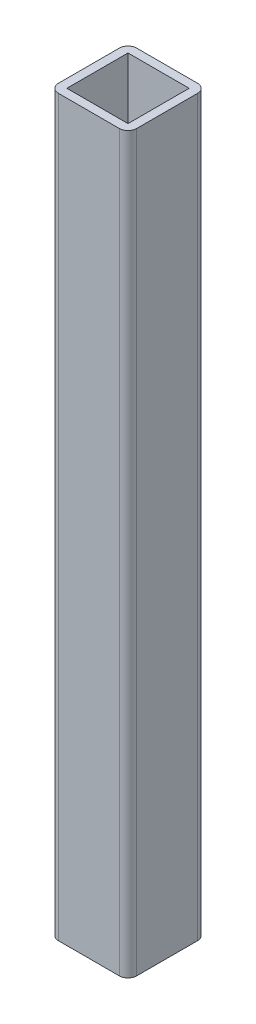
SolidWorks part; units mm, degrees
material "Plain Carbon Steel"
ref_plane "Front Plane" through (0, 0, 0) normal (0, 0, 1) x (1, 0, 0)
ref_plane "Top Plane" through (0, 0, 0) normal (0, 1, 0) x (1, 0, 0)
ref_plane "Right Plane" through (0, 0, 0) normal (1, 0, 0) x (0, 0, -1)
sketch "Sketch1" plane through (0, 0, 0) normal (0, 1, 0) x (1, 0, 0)
  line L1 (2.8, 0) -> (22.8, 0)
  line L2 (0, -2.8) -> (0, -22.8)
  line L3 (2.8, -25.6) -> (22.8, -25.6)
  line L4 (25.6, -2.8) -> (25.6, -22.8)
  arc A0 (22.8, 0) -> (25.6, -2.8) centre (22.8, -2.8) cw
  arc A1 (22.8, -25.6) -> (25.6, -22.8) centre (22.8, -22.8) ccw
  arc A2 (0, -22.8) -> (2.8, -25.6) centre (2.8, -22.8) ccw
  arc A3 (2.8, 0) -> (0, -2.8) centre (2.8, -2.8) ccw
  point P7 (25.6, 0)
  point P10 (25.6, -25.6)
  point P15 (0, 0)
  dimension "D2" = 2.8
  dimension "D1" = 25.6
extrude "Boss-Extrude1" add sketch "Sketch1" along normal blind 240
sketch "Sketch3" plane through (0, 0, 0) normal (0, -1, 0) x (-1, 0, 0)
  line L4 (-2.8, -2.8) -> (-22.8, -2.8)
  line L5 (-2.8, -2.8) -> (-2.8, -22.8)
  line L6 (-2.8, -22.8) -> (-22.8, -22.8)
  line L7 (-22.8, -2.8) -> (-22.8, -22.8)
  line L8 (-2.8, -2.8) -> (-22.8, -22.8) construction
  line L9 (-2.8, -22.8) -> (-22.8, -2.8) construction
  point P6 (-12.8, -12.8)
extrude "Cut-Extrude1" cut sketch "Sketch3" against normal blind 1040.5
